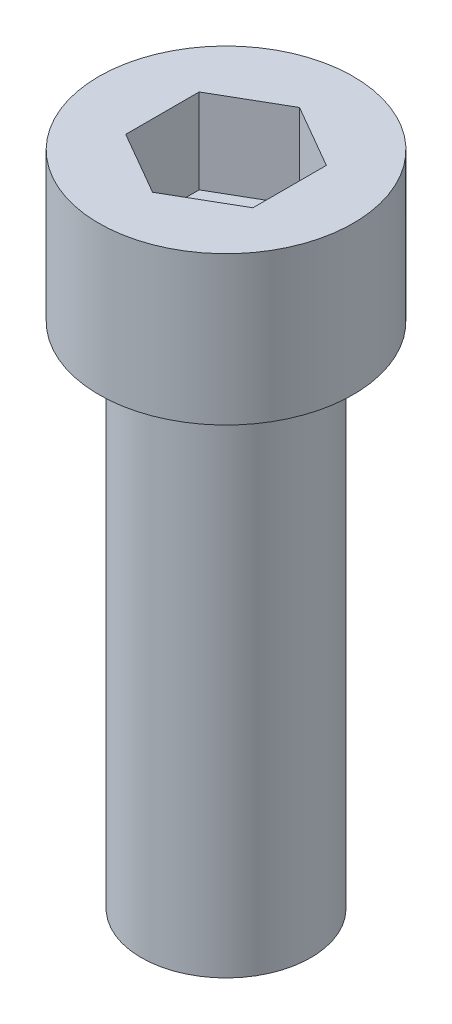
SolidWorks part; units mm, degrees
ref_plane "Front Plane" through (0, 0, 0) normal (0, 0, 1) x (1, 0, 0)
ref_plane "Top Plane" through (0, 0, 0) normal (0, 1, 0) x (1, 0, 0)
ref_plane "Right Plane" through (0, 0, 0) normal (1, 0, 0) x (0, 0, -1)
sketch "Sketch1" plane through (0, 0, 0) normal (0, 0, 1) x (1, 0, 0)
  line L0 (0, 15.5) -> (0, 0)
  line L1 (0, 0) -> (2, 0)
  line L2 (2, 0) -> (2, 12)
  line L3 (2, 12) -> (3, 12)
  line L4 (3, 12) -> (3, 15.5)
  line L5 (3, 15.5) -> (0, 15.5)
  dimension "D1" = 2
  dimension "D2" = 3
  dimension "D3" = 3.5
  dimension "D4" = 12
revolve "Revolve1" add sketch "Sketch1" angle 360 about L0
sketch "Sketch2" plane through (0, 15.5, 0) normal (0, 1, 0) x (1, 0, 0)
  line L1 (0, -1.7321) -> (1.5, -0.866)
  line L2 (1.5, -0.866) -> (1.5, 0.866)
  line L3 (1.5, 0.866) -> (0, 1.7321)
  line L4 (0, 1.7321) -> (-1.5, 0.866)
  line L5 (-1.5, 0.866) -> (-1.5, -0.866)
  line L6 (-1.5, -0.866) -> (0, -1.7321)
  circle A0 centre (0, 0) radius 1.5 construction
  dimension "D1" = 3
extrude "Cut-Extrude1" cut sketch "Sketch2" against normal blind 2
